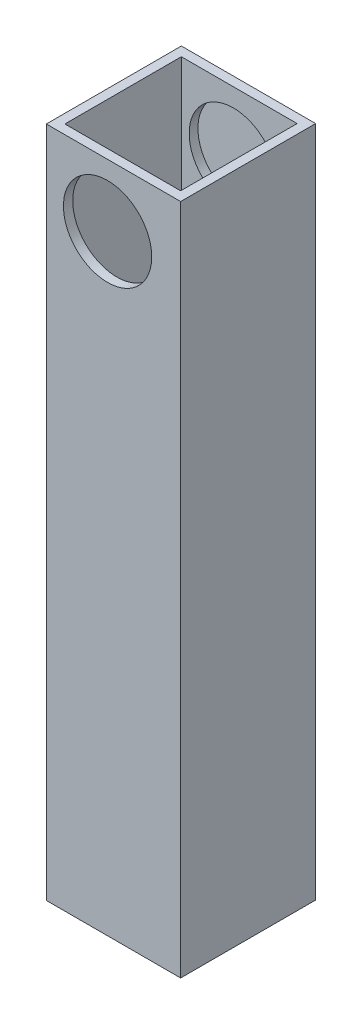
SolidWorks part; units mm, degrees
ref_plane "Front Plane" through (0, 0, 0) normal (0, 0, 1) x (1, 0, 0)
ref_plane "Top Plane" through (0, 0, 0) normal (0, 1, 0) x (1, 0, 0)
ref_plane "Right Plane" through (0, 0, 0) normal (1, 0, 0) x (0, 0, -1)
sketch "Sketch1" plane through (0, 0, 0) normal (0, 1, 0) x (1, 0, 0)
  line L0 (0, 0) -> (25.3664, 0)
  line L1 (25.3664, 0) -> (25.3664, -25.5038)
  line L2 (25.3664, -25.5038) -> (0, -25.5038)
  line L3 (0, -25.5038) -> (0, 0)
extrude "Boss-Extrude1" add sketch "Sketch1" along normal blind 127
sketch "Sketch2" plane through (0, 0, 25.5038) normal (0, 0, 1) x (1, 0, 0)
  circle A0 centre (11.5686, 115.2011) radius 8.3389
extrude "Cut-Extrude1" cut sketch "Sketch2" against normal blind 25.4 contours A0
sketch "Sketch3" plane through (0, 127, 0) normal (0, 1, 0) x (1, 0, 0)
  line L0 (25.3664, -25.5038) -> (25.3664, 0) construction
  line L1 (1.7526, -23.7512) -> (23.6138, -23.7512)
  line L2 (1.7526, -23.7512) -> (1.7526, -1.7526)
  line L3 (1.7526, -1.7526) -> (23.6138, -1.7526)
  line L4 (23.6138, -23.7512) -> (23.6138, -1.7526)
  line L5 (1.7526, -23.7512) -> (23.6138, -1.7526) construction
  line L6 (1.7526, -1.7526) -> (23.6138, -23.7512) construction
  line L7 (0, -25.5038) -> (25.3664, -25.5038) construction
  line L8 (0, 0) -> (0, -25.5038) construction
  line L9 (25.3664, 0) -> (0, 0) construction
  point P0 (12.6832, -12.7519)
  point P7 (12.6832, -23.7512)
  dimension "D1" = 1.7526
  dimension "D2" = 1.7526
  dimension "D3" = 1.7526
  dimension "D4" = 1.7526
extrude "Cut-Extrude2" cut sketch "Sketch3" against normal blind 127 contours L2 L1 L4 L3
